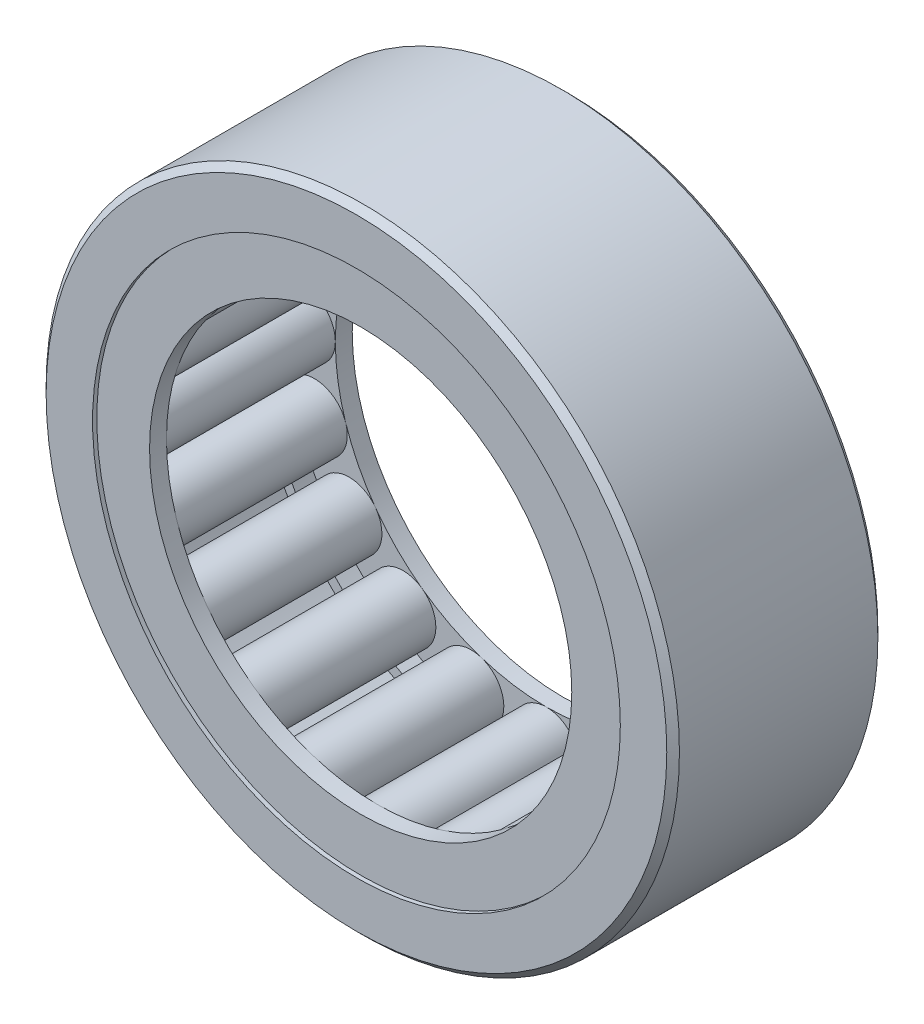
SolidWorks part; units mm, degrees
ref_plane "Front" through (0, 0, 0) normal (0, 0, 1) x (1, 0, 0)
ref_plane "Top" through (0, 0, 0) normal (0, 1, 0) x (1, 0, 0)
ref_plane "Right" through (0, 0, 0) normal (1, 0, 0) x (0, 0, -1)
sketch "Sketch1" plane through (0, 0, 0) normal (1, 0, 0) x (0, 0, -1)
  line L0 (0, 0) -> (0, 16.51) construction
  line L1 (-3.81, 16.51) -> (3.81, 16.51)
  line L2 (3.81, 16.51) -> (3.81, 15.875)
  line L3 (-3.81, 16.51) -> (-3.81, 15.875)
  line L4 (3.81, 15.875) -> (6.35, 15.875)
  line L5 (-3.81, 15.875) -> (-6.35, 15.875)
  line L6 (6.35, 15.875) -> (6.35, 19.05)
  line L7 (-6.35, 15.875) -> (-6.35, 19.05)
  line L8 (6.35, 19.05) -> (-6.35, 19.05)
  line L9 (0, 0) -> (24.5379, 0) construction
  point P11 (0, 19.05)
  dimension "D1" = 12.7
  dimension "D2" = 31.75
  dimension "D3" = 2.54
  dimension "D4" = 33.02
  dimension "D5" = 38.1
revolve "Revolve1" add sketch "Sketch1" angle 360 about L9
chamfer "Chamfer1" distance 0.381 angle 45 2 edges at (19.05, 0, -6.35) (19.05, 0, 6.35)
sketch "Sketch2" plane through (0, 0, 0) normal (0, 0, 1) x (1, 0, 0)
  circle A0 centre (0, 0) radius 12.7 construction
  circle A1 centre (0, 14.6685) radius 1.9685
  dimension "D1" = 25.4
  dimension "D2" = 3.937
extrude "Boss-Extrude1" add sketch "Sketch2" along normal mid plane 10.16
pattern_circular "CirPattern1" count 20 over 360 about axis through (0, 0, 0) along (0, 0, 1) of "Boss-Extrude1"
sketch "Sketch3" plane through (0, 0, 5.08) normal (0, 0, 1) x (1, 0, 0)
  circle A0 centre (0, 0) radius 12.7
  circle A1 centre (0, 0) radius 15.875 construction
  circle A2 centre (0, 0) radius 15.875
  arc A3 (-1.616, 15.7925) -> (1.616, 15.7925) centre (0, 14.6685) ccw construction
extrude "Boss-Extrude2" add sketch "Sketch3" along normal blind 1.016
mirror "Mirror1" about plane through (0, 0, 0) normal (0, 0, 1) of "Boss-Extrude2"
